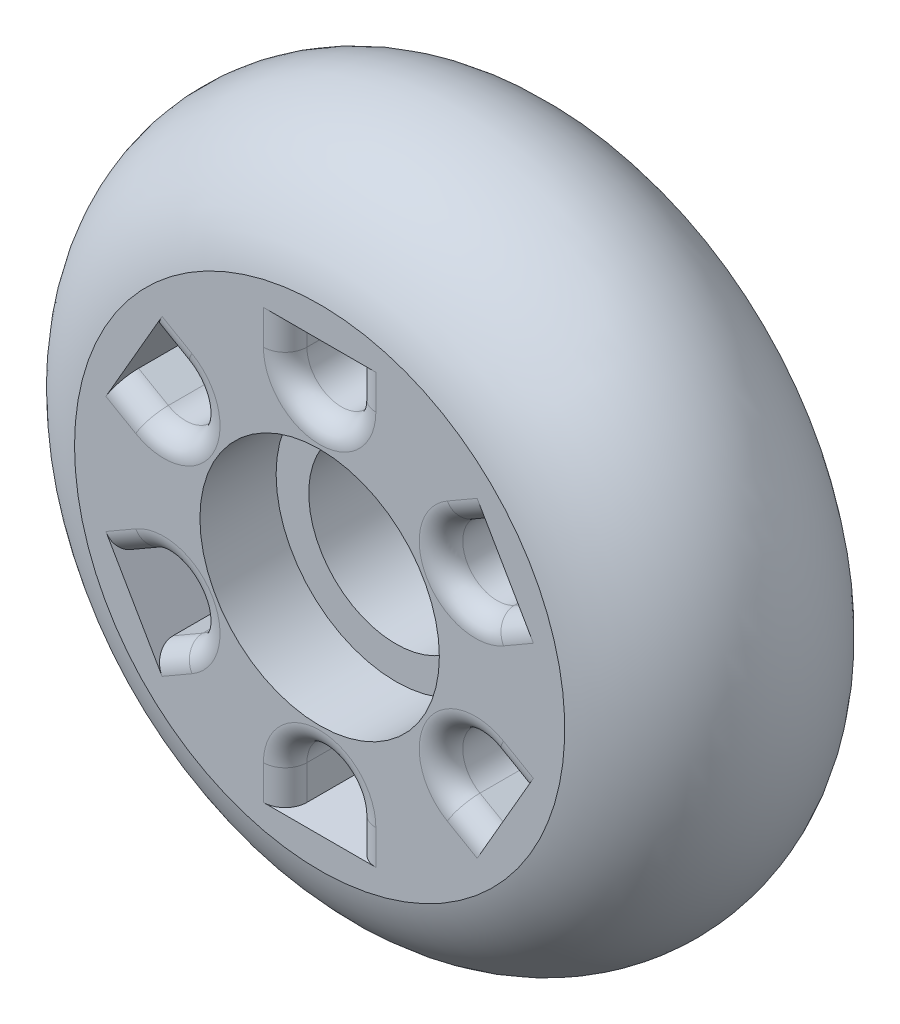
SolidWorks part; units mm, degrees
ref_plane "Front Plane" through (0, 0, 0) normal (0, 0, 1) x (1, 0, 0)
ref_plane "Top Plane" through (0, 0, 0) normal (0, 1, 0) x (1, 0, 0)
ref_plane "Right Plane" through (0, 0, 0) normal (1, 0, 0) x (0, 0, -1)
sketch "Sketch1" plane through (0, 0, 0) normal (1, 0, 0) x (0, 0, -1)
  line L1 (12, 0) -> (-12, 0)
  line L2 (12, 0) -> (12, 22.5212)
  line L4 (-12, 0) -> (-12, 22.5212)
  arc A0 (-12, 22.5212) -> (12, 22.5212) centre (0, 19.6647) cw
  dimension "D2" = 24
revolve "Revolve1" add sketch "Sketch1" angle 360 about L1
sketch "Sketch2" plane through (0, 0, 12) normal (0, 0, 1) x (1, 0, 0)
  circle A0 centre (0, 0) radius 11
extrude "Cut-Extrude1" cut sketch "Sketch2" against normal blind 7
sketch "Sketch3" plane through (0, 0, -12) normal (0, 0, -1) x (-1, 0, 0)
  circle A0 centre (0, 0) radius 11
extrude "Cut-Extrude2" cut sketch "Sketch3" against normal blind 7
sketch "Sketch4" plane through (0, 0, 5) normal (0, 0, 1) x (1, 0, 0)
  circle A0 centre (0, 0) radius 8
extrude "Cut-Extrude3" cut sketch "Sketch4" against normal up to next
sketch "Sketch6" plane through (0, 0, 12) normal (0, 0, 1) x (1, 0, 0)
  line L0 (-3.1656, 16.5301) -> (-3.1656, 19.6957)
  line L1 (-3.1656, 19.6957) -> (3.1656, 19.6957)
  line L2 (3.1656, 19.6957) -> (3.1656, 16.5301)
  arc A0 (-3.1656, 16.5301) -> (3.1656, 16.5301) centre (0, 16.5301) ccw
  point P1 (0, 0)
extrude "Cut-Extrude4" cut sketch "Sketch6" against normal up to next
pattern_circular "CirPattern1" count 6 over 360 about axis through (0, 0, 0) along (0, 0, 1) of "Cut-Extrude4"
fillet "Fillet1" radius 2 36 edges at (-11.574, -6.6822, 12) (-11.574, -6.6822, -12) (0, -13.3645, 12) (0, -13.3645, -12) (11.574, -6.6822, 12) (11.574, -6.6822, -12) (11.574, 6.6822, 12) (11.574, 6.6822, -12) (0, 13.3645, 12) (0, 13.3645, -12) (-11.574, 6.6822, 12) (-11.574, 6.6822, -12) (-14.1034, -11.798, -12) (-17.269, -6.3149, -12) (-14.1034, -11.798, 12) (-17.269, -6.3149, 12) (3.1656, -18.1129, -12) (-3.1656, -18.1129, -12) (3.1656, -18.1129, 12) (-3.1656, -18.1129, 12) (17.269, -6.3149, -12) (14.1034, -11.798, -12) (17.269, -6.3149, 12) (14.1034, -11.798, 12) (14.1034, 11.798, -12) (17.269, 6.3149, -12) (14.1034, 11.798, 12) (17.269, 6.3149, 12) (-3.1656, 18.1129, -12) (3.1656, 18.1129, -12) (-3.1656, 18.1129, 12) (3.1656, 18.1129, 12) (-17.269, 6.3149, -12) (-14.1034, 11.798, -12) (-17.269, 6.3149, 12) (-14.1034, 11.798, 12)
